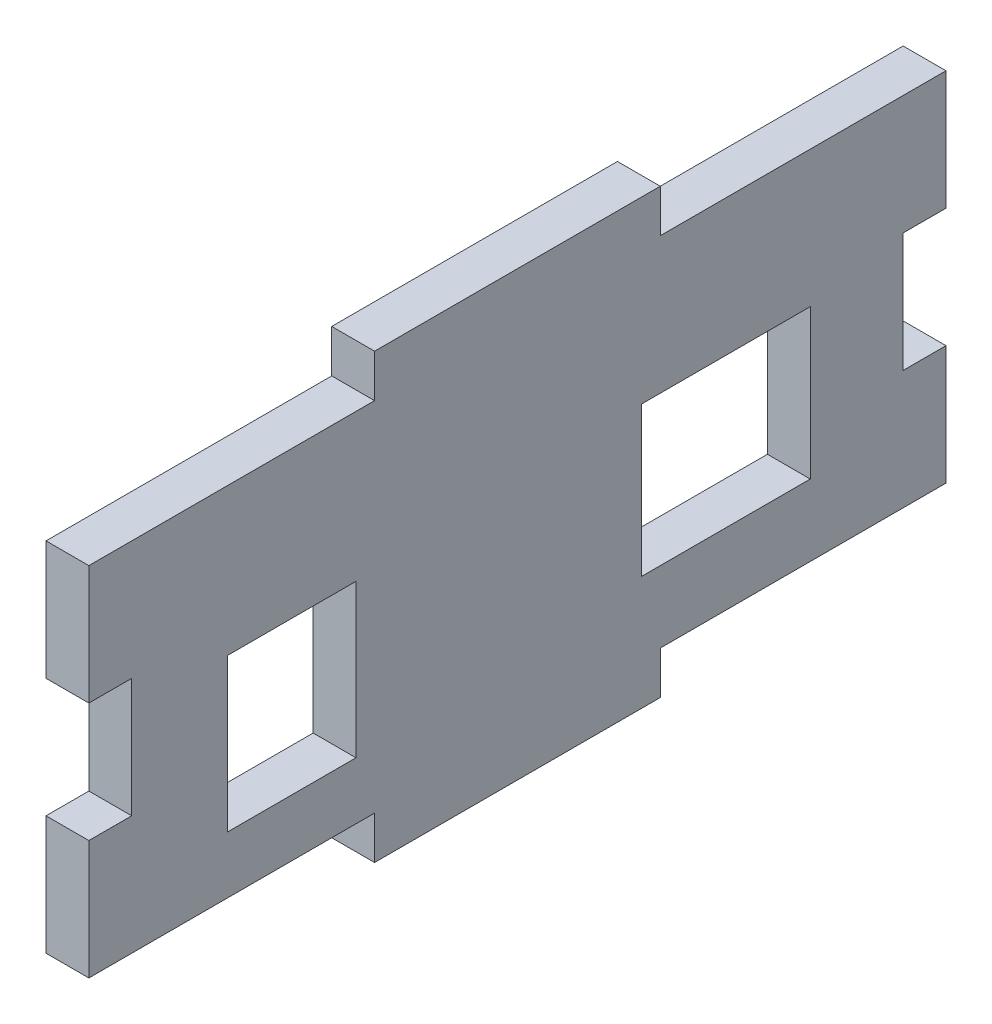
SolidWorks part; units mm, degrees
ref_plane "Front Plane" through (0, 0, 0) normal (0, 0, 1) x (1, 0, 0)
ref_plane "Top Plane" through (0, 0, 0) normal (0, 1, 0) x (1, 0, 0)
ref_plane "Right Plane" through (0, 0, 0) normal (1, 0, 0) x (0, 0, -1)
sketch "Sides" plane through (0, 0, 0) normal (1, 0, 0) x (0, 0, -1)
  line L0 (0, 16.6667) -> (0, 25)
  line L1 (0, 0) -> (20, 0)
  line L2 (0, 0) -> (0, 8.3333)
  line L3 (0, 25) -> (20, 25)
  line L4 (60, 0) -> (60, 8.3333)
  line L5 (0, 16.6667) -> (3, 16.6667)
  line L6 (40, 25) -> (60, 25)
  line L7 (0, 8.3333) -> (3, 8.3333)
  line L8 (3, 16.6667) -> (3, 8.3333)
  line L9 (40, 0) -> (60, 0)
  line L10 (20, 25) -> (20, 28)
  line L11 (20, 28) -> (40, 28)
  line L12 (40, 25) -> (40, 28)
  line L13 (60, 16.6667) -> (60, 25)
  line L14 (40, 0) -> (40, -3)
  line L15 (20, 0) -> (20, -3)
  line L16 (20, -3) -> (40, -3)
  line L17 (60, 16.6667) -> (57, 16.6667)
  line L18 (60, 8.3333) -> (57, 8.3333)
  line L19 (57, 16.6667) -> (57, 8.3333)
  line L21 (50.5, 15.45) -> (38.7, 15.45)
  line L22 (50.5, 15.45) -> (50.5, 5)
  line L23 (50.5, 5) -> (38.7, 5)
  line L24 (38.7, 15.45) -> (38.7, 5)
  line L25 (18.7, 14.7) -> (9.7, 14.7)
  line L26 (18.7, 14.7) -> (18.7, 4)
  line L27 (18.7, 4) -> (9.7, 4)
  line L28 (9.7, 14.7) -> (9.7, 4)
  dimension "D1" = 25
  dimension "D2" = 60
  dimension "D3" = 8.3333
  dimension "D4" = 8.3333
  dimension "D5" = 3
  dimension "D6" = 20
  dimension "D7" = 3
  dimension "D8" = 20
  dimension "D9" = 10.45
  dimension "D10" = 11.8
  dimension "D11" = 10.7
  dimension "D12" = 9
  dimension "D13" = 20
  dimension "D14" = 1
  dimension "D15" = 9.5
  dimension "D16" = 20
  dimension "D17" = 20
  dimension "D18" = 4
extrude "Sides Extruded" add sketch "Sides" along normal blind 3
